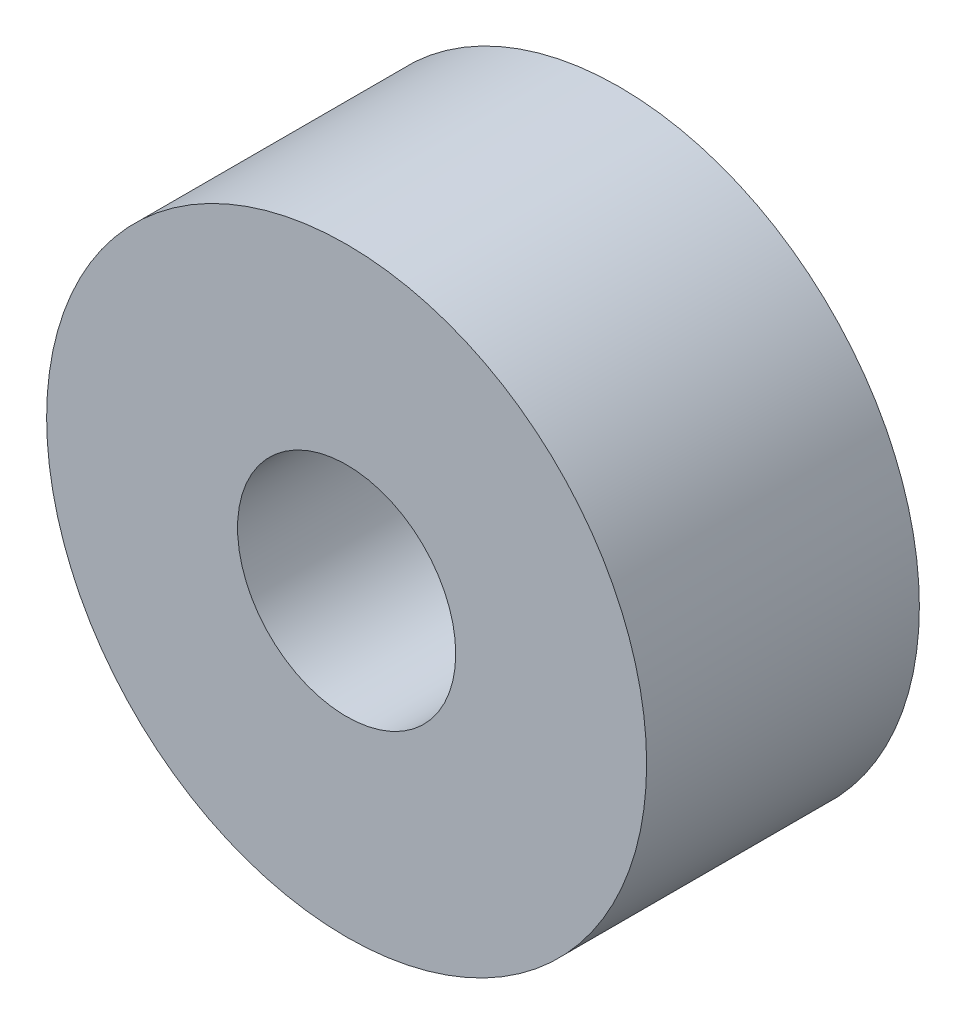
SolidWorks part; units mm, degrees
ref_plane "Спереди" through (0, 0, 0) normal (0, 0, 1) x (1, 0, 0)
ref_plane "Сверху" through (0, 0, 0) normal (0, 1, 0) x (1, 0, 0)
ref_plane "Справа" through (0, 0, 0) normal (1, 0, 0) x (0, 0, -1)
sketch "Эскиз1" plane through (0, 0, 0) normal (0, 0, 1) x (1, 0, 0)
  circle A0 centre (0, 0) radius 4
  circle A1 centre (0, 0) radius 11
extrude "Бобышка-Вытянуть1" add sketch "Эскиз1" along normal blind 10
